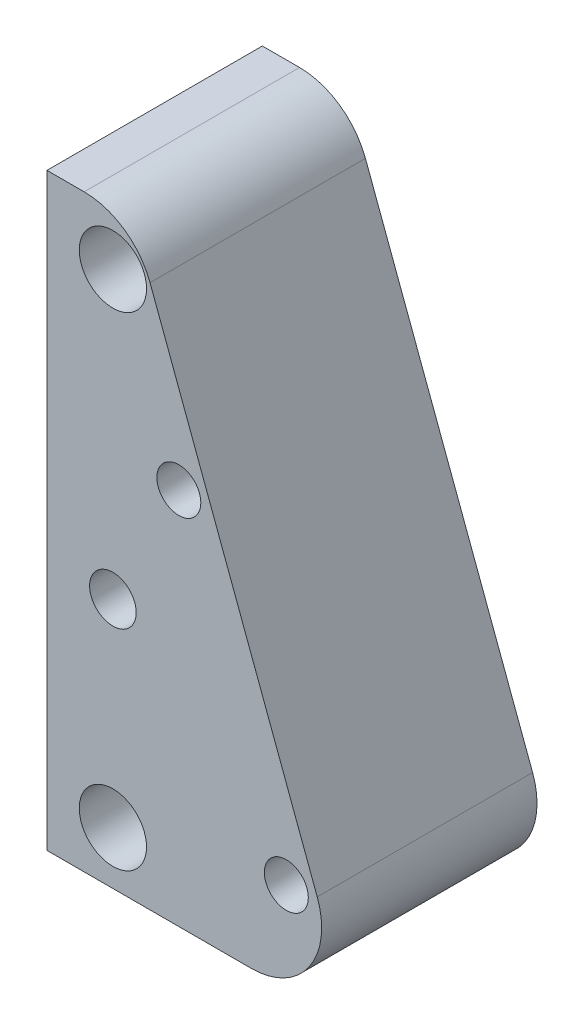
SolidWorks part; units mm, degrees
ref_plane "Płaszczyzna przednia" through (0, 0, 0) normal (0, 0, 1) x (1, 0, 0)
ref_plane "Płaszczyzna górna" through (0, 0, 0) normal (0, 1, 0) x (1, 0, 0)
ref_plane "Płaszczyzna prawa" through (0, 0, 0) normal (1, 0, 0) x (0, 0, -1)
sketch "Szkic1" plane through (0, 0, 0) normal (0, 0, 1) x (1, 0, 0)
  line L0 (-15, -57) -> (-15, 77)
  line L1 (15, 29) -> (15, -84.3544) construction
  line L2 (15, 29) -> (39.4573, -36.5884) construction
  line L3 (-15, 77) -> (4.5721, 77)
  line L4 (4.5721, 77) -> (54.5394, -57)
  line L5 (54.5394, -57) -> (-15, -57)
  circle A0 centre (0, 65) radius 7.65
  circle A1 centre (0, -45) radius 7.65
  circle A2 centre (0, 0) radius 5.3
  circle A3 centre (15, 29) radius 5
  circle A4 centre (39.4573, -36.5884) radius 5
  point P14 (0, 0)
  dimension "D1" = 15.3
  dimension "D2" = 110
  dimension "D4" = 10.6
  dimension "D7" = 20.45
  dimension "D8" = 10
  dimension "D9" = 70
  dimension "D3" = 45
  dimension "D5" = 134
  dimension "D6" = 15
  dimension "D10" = 15
  dimension "D11" = 74
  dimension "D12" = 7
  dimension "D13" = 12
extrude "Dodanie-wyciągnięcie1" add sketch "Szkic1" along normal blind 49
fillet "Zaokrąglenie1" radius 16 2 edges at (4.5721, 77, 24.5) (54.5394, -57, 24.5)
sketch "Szkic2" plane through (0, 0, 0) normal (0, 0, -1) x (-1, 0, 0)
  circle A0 centre (0, 0) radius 8 construction
  circle A1 centre (0, 0) radius 11
  dimension "D1" = 16
extrude "Wytnij-wyciągnięcie1" cut sketch "Szkic2" against normal blind 4
sketch "Szkic3" plane through (0, 0, 4) normal (0, 0, -1) x (-1, 0, 0)
  circle A0 centre (0, 0) radius 8 construction
  circle A1 centre (0, 8) radius 1.21
  circle A2 centre (8, 0) radius 1.21
  circle A3 centre (0, -8) radius 1.21
  circle A4 centre (-8, 0) radius 1.21
  point P14 (0, 0)
  dimension "D1" = 16
  dimension "D2" = 2.42
  dimension "D3" = 4
extrude "Wytnij-wyciągnięcie2" cut sketch "Szkic3" against normal blind 15
